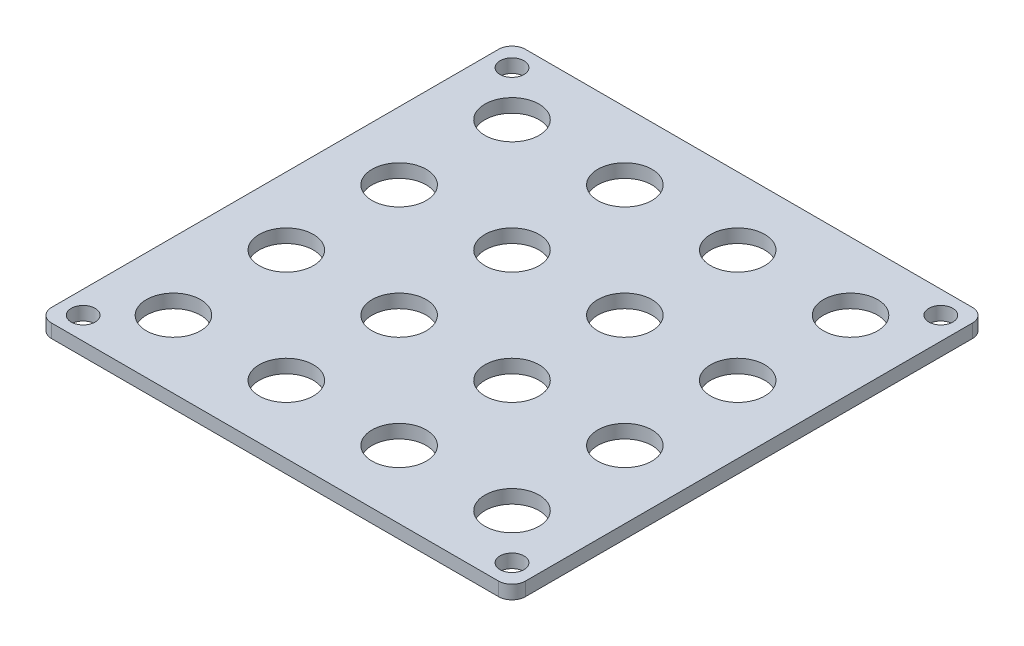
SolidWorks part; units mm, degrees
material "6061-T6 (SS)"
ref_plane "Front Plane" through (0, 0, 0) normal (0, 0, 1) x (1, 0, 0)
ref_plane "Top Plane" through (0, 0, 0) normal (0, 1, 0) x (1, 0, 0)
ref_plane "Right Plane" through (0, 0, 0) normal (1, 0, 0) x (0, 0, -1)
sketch "Sketch1" plane through (0, 0, 0) normal (0, 1, 0) x (1, 0, 0)
  line L0 (25, 0) -> (0, 0) construction
  line L1 (0, 0) -> (0, -25) construction
  line L2 (0, -50) -> (0, -75) construction
  line L3 (0, -75) -> (75, -75) construction
  line L9 (75, -75) -> (75, -50) construction
  line L10 (25, -25) -> (50, -50) construction
  line L12 (90, -90) -> (-15, -90)
  line L13 (90, -90) -> (90, 15)
  line L14 (90, 15) -> (-15, 15)
  line L15 (-15, -90) -> (-15, 15)
  line L16 (90, -90) -> (-15, 15) construction
  line L17 (90, 15) -> (-15, -90) construction
  circle A0 centre (0, 0) radius 6
  circle A1 centre (25, 0) radius 6
  circle A2 centre (50, 0) radius 6
  circle A3 centre (75, 0) radius 6
  circle A4 centre (25, -25) radius 6
  circle A5 centre (50, -25) radius 6
  circle A6 centre (75, -25) radius 6
  circle A7 centre (25, -50) radius 6
  circle A8 centre (50, -50) radius 6
  circle A9 centre (75, -50) radius 6
  circle A10 centre (0, -25) radius 6
  circle A11 centre (0, -50) radius 6
  circle A12 centre (0, -75) radius 6
  circle A14 centre (75, -75) radius 6
  circle A15 centre (25, -75) radius 6
  circle A16 centre (50, -75) radius 6
  point P31 (37.5, -37.5)
  dimension "D1" = 12
  dimension "D4" = 25
  dimension "D6" = 15
  dimension "D7" = 15
  dimension "D2" = 4
  dimension "D3" = 3
extrude "Boss-Extrude1" add sketch "Sketch1" along normal blind 3
sketch "Screw Positions" plane through (0, 3, 0) normal (0, 1, 0) x (1, 0, 0)
  line L0 (25, -25) -> (50, -50) construction
  line L2 (85, -85) -> (-10, -85)
  line L3 (85, -85) -> (85, 10)
  line L4 (85, 10) -> (-10, 10)
  line L5 (-10, -85) -> (-10, 10)
  line L6 (85, -85) -> (-10, 10) construction
  line L7 (85, 10) -> (-10, -85) construction
  line L9 (90, 15) -> (-15, 15) construction
  line L10 (-15, 15) -> (-15, -90) construction
  point P4 (37.5, -37.5)
  dimension "D1" = 5
  dimension "D2" = 5
hole_wizard "M5 Clearance Hole1" positions "Sketch3" profile "Sketch4" hole size "M5" standard "ANSI Metric" end condition up to next
sketch "Sketch3" plane through (0, 3, 0) normal (0, 1, 0) x (1, 0, 0)
  point P0 (-10, 10)
  point P3 (-10, -85)
  point P6 (85, -85)
  point P9 (85, 10)
sketch "Sketch4" plane through (-10, 3, -10) normal (1, 0, 0) x (0, 0, 1)
  line L0 (0, 0) -> (0, 3)
  line L1 (0, 3) -> (2.65, 3)
  line L2 (2.65, 3) -> (2.65, 0)
  line L5 (2.65, 0) -> (0, 0)
  line L11 (0, -6.35) -> (0, 107.95) construction
  dimension "Thru Hole Dia." = 5.3
  dimension "Thru Hole Depth" = 3
fillet "Fillet2" radius 3 4 edges at (-15, 1.5, -15) (90, 1.5, -15) (90, 1.5, 90) (-15, 1.5, 90)
